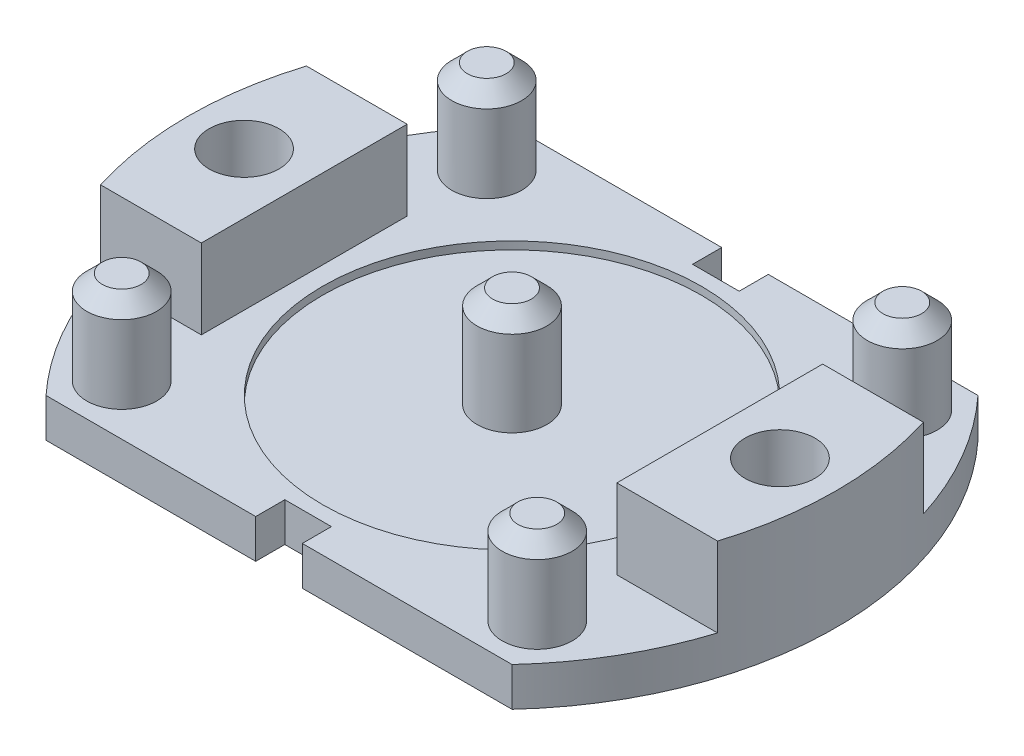
SolidWorks part; units mm, degrees
ref_plane "Front Plane" through (0, 0, 0) normal (0, 0, 1) x (1, 0, 0)
ref_plane "Top Plane" through (0, 0, 0) normal (0, 1, 0) x (1, 0, 0)
ref_plane "Right Plane" through (0, 0, 0) normal (1, 0, 0) x (0, 0, -1)
sketch "Croquis1" plane through (0, 0, 0) normal (0, 1, 0) x (1, 0, 0)
  line L0 (-8.35, 0) -> (8.35, 0) construction
  line L2 (0, -6.1883) -> (0, 7.7921) construction
  line L5 (6, 6) -> (0.6, 6)
  line L7 (-6, -6) -> (-0.6, -6)
  line L9 (-0.6, 6) -> (-0.6, 5.25)
  line L10 (-0.6, 5.25) -> (0.6, 5.25)
  line L11 (0.6, 5.25) -> (0.6, 6)
  line L13 (-0.6, 6) -> (-6, 6)
  line L14 (-0.6, -6) -> (-0.6, -5.25)
  line L15 (-0.6, -5.25) -> (0.6, -5.25)
  line L16 (0.6, -5.25) -> (0.6, -6)
  line L18 (0.6, -6) -> (6, -6)
  line L19 (-6, 0) -> (-6, -6) [skipped]
  line L20 (6, -6) -> (6, 0) [skipped]
  circle A0 centre (0, 0) radius 6 construction
  arc A3 (-6, 6) -> (-6, -6) centre (0.4846, 0) ccw
  arc A4 (6, -6) -> (6, 6) centre (-0.4846, 0) ccw
  point P16 (0, 0)
  point P25 (0, -5.25)
  dimension "D3" = 1.2
  dimension "D9" = 17.6691
  dimension "D5" = 17.6691
  dimension "D1" = 12
  dimension "D2" = 5.4
  dimension "D4" = 0.75
  dimension "D6" = 5.4
  dimension "D7" = 1.2
  dimension "D8" = 0.75
  dimension "D10" = 16.7
extrude "Saliente-Extruir1" add sketch "Croquis1" along normal blind 1
sketch "Croquis3" plane through (0, 1, 0) normal (0, 1, 0) x (1, 0, 0)
  circle A0 centre (0, 0) radius 4.875
  dimension "D1" = 9.75
extrude "Cortar-Extruir1" cut sketch "Croquis3" against normal blind 0.2
sketch "Croquis4" plane through (0, 0, 0) normal (0, -1, 0) x (1, 0, 0)
  line L0 (-6, 6) -> (-0.6, 6) construction
  line L1 (5.35, 2.65) -> (5.35, -2.65)
  line L2 (-11.4229, 0) -> (17.605, 0) construction
  line L3 (5.35, 2.65) -> (7.9432, 2.65)
  line L4 (5.35, -2.65) -> (7.9432, -2.65)
  line L5 (-5.35, -2.65) -> (-5.35, 2.65)
  line L6 (-5.35, 2.65) -> (-7.9432, 2.65)
  line L7 (-5.35, -2.65) -> (-7.9432, -2.65)
  circle A0 centre (0, 0) radius 0.9
  circle A1 centre (-5.35, 4.7) radius 0.9
  circle A2 centre (-5.35, -4.7) radius 0.9
  circle A3 centre (5.35, 4.7) radius 0.9
  circle A4 centre (5.35, -4.7) radius 0.9
  arc A5 (6, -6) -> (6, 6) centre (-0.4846, 0) ccw construction
  arc A6 (7.9432, -2.65) -> (7.9432, 2.65) centre (-0.4846, 0) ccw
  arc A7 (-6, 6) -> (-6, -6) centre (0.4846, 0) ccw construction
  arc A8 (-7.9432, 2.65) -> (-7.9432, -2.65) centre (0.4846, 0) ccw
  point P21 (5.35, 0)
  point P29 (-5.35, 0)
  dimension "D1" = 1.8
  dimension "D2" = 1.8
  dimension "D5" = 1.8
  dimension "D8" = 1.8
  dimension "D11" = 1.8
  dimension "D3" = 1.3
  dimension "D4" = 0.65
  dimension "D6" = 0.65
  dimension "D7" = 1.3
  dimension "D9" = 0.65
  dimension "D10" = 1.3
  dimension "D12" = 0.65
  dimension "D13" = 1.3
  dimension "D14" = 5.3
  dimension "D15" = 5.3
extrude "Saliente-Extruir2" add sketch "Croquis4" against normal blind 3.4
chamfer "Chaflán1" distance 0.4 angle 45 5 edges at (5.35, 3.4, 3.8) (-5.35, 3.4, 3.8) (5.35, 3.4, -5.6) (-5.35, 3.4, -5.6) (0, 3.4, -0.9)
sketch "Croquis5" plane through (0, 3.4, 0) normal (0, 1, 0) x (1, 0, 0)
  line L0 (-10.151, 0) -> (9.4491, 0) construction
  line L2 (-5.35, 2.65) -> (-5.35, -2.65) construction
  line L3 (5.35, 2.65) -> (5.35, -2.65) construction
  circle A0 centre (-6.9, 0) radius 0.9
  circle A1 centre (6.9, 0) radius 0.9
  point P7 (6, 0)
  point P9 (-6, 0)
  dimension "D1" = 1.8
  dimension "D2" = 1.8
  dimension "D3" = 0.65
  dimension "D4" = 0.65
extrude "Cortar-Extruir2" cut sketch "Croquis5" against normal up to surface (2.4 mm away) up to face at (0, 1, 0)
sketch "Croquis6" plane through (0, 3.4, 0) normal (0, 1, 0) x (1, 0, 0)
  line L0 (-5.35, 2.65) -> (-7.9432, 2.65) construction
  line L1 (-7.9432, -2.65) -> (-5.35, -2.65) construction
  line L2 (-5.35, -2.65) -> (-5.35, 2.65) construction
  line L3 (5.35, -2.65) -> (7.9432, -2.65) construction
  line L4 (7.9432, 2.65) -> (5.35, 2.65) construction
  line L5 (5.35, 2.65) -> (5.35, -2.65) construction
  line L6 (-5.35, 2.65) -> (-7.9432, 2.65)
  line L7 (-7.9432, -2.65) -> (-5.35, -2.65)
  line L8 (-5.35, -2.65) -> (-5.35, 2.65)
  line L9 (5.35, -2.65) -> (7.9432, -2.65)
  line L10 (7.9432, 2.65) -> (5.35, 2.65)
  line L11 (5.35, 2.65) -> (5.35, -2.65)
  arc A0 (-7.9432, 2.65) -> (-7.9432, -2.65) centre (0.4846, 0) ccw construction
  arc A1 (7.9432, -2.65) -> (7.9432, 2.65) centre (-0.4846, 0) ccw construction
  arc A2 (-7.9432, 2.65) -> (-7.9432, -2.65) centre (0.4846, 0) ccw
  arc A3 (7.9432, -2.65) -> (7.9432, 2.65) centre (-0.4846, 0) ccw
extrude "Cortar-Extruir3" cut sketch "Croquis6" against normal blind 0.35
